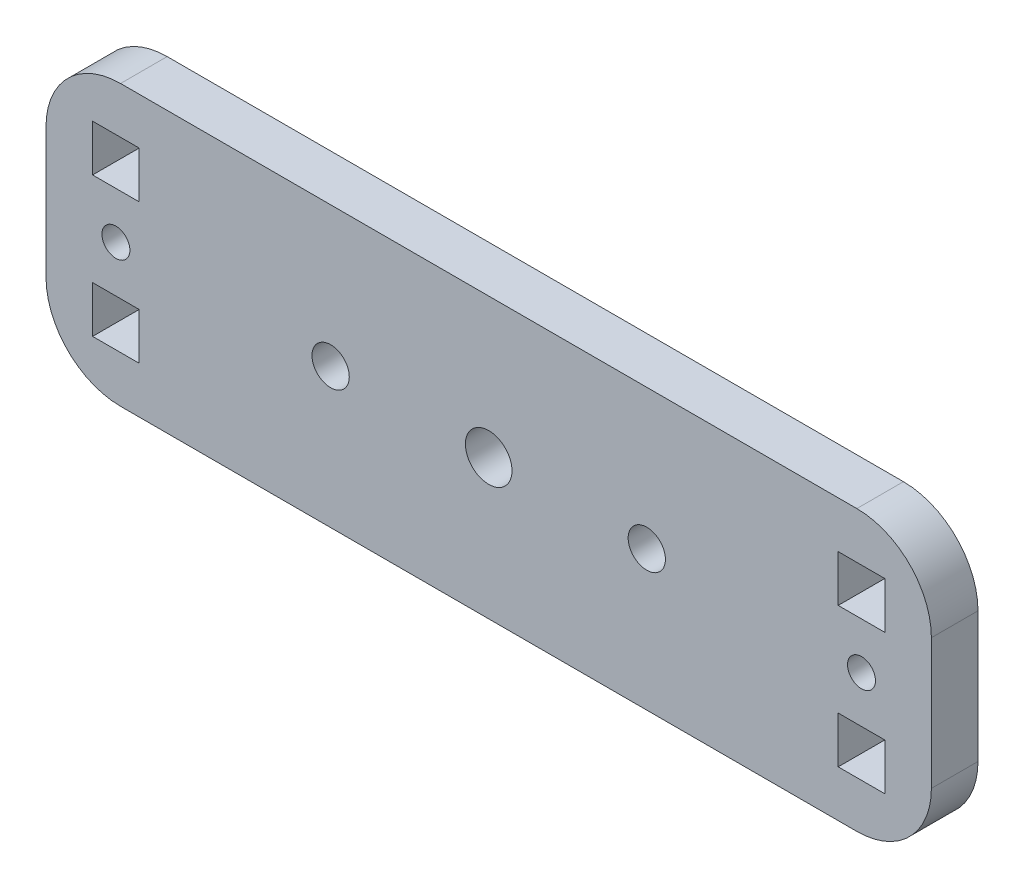
SolidWorks part; units mm, degrees
ref_plane "Plan de face" through (0, 0, 0) normal (0, 0, 1) x (1, 0, 0)
ref_plane "Plan de dessus" through (0, 0, 0) normal (0, 1, 0) x (1, 0, 0)
ref_plane "Plan de droite" through (0, 0, 0) normal (1, 0, 0) x (0, 0, -1)
sketch "Esquisse1" plane through (0, 0, 0) normal (0, 0, 1) x (1, 0, 0)
  line L0 (0, 15) -> (95, 15) construction
  line L1 (8, 0) -> (87, 0)
  line L2 (0, 8) -> (0, 22)
  line L3 (8, 30) -> (87, 30)
  line L4 (95, 8) -> (95, 22)
  line L5 (5, 25) -> (10, 25)
  line L6 (5, 25) -> (5, 20)
  line L7 (5, 20) -> (10, 20)
  line L8 (10, 25) -> (10, 20)
  line L17 (85, 25) -> (90, 25)
  line L18 (85, 25) -> (85, 20)
  line L19 (85, 20) -> (90, 20)
  line L20 (90, 25) -> (90, 20)
  line L21 (90, 5) -> (90, 10)
  line L22 (85, 10) -> (90, 10)
  line L23 (85, 5) -> (85, 10)
  line L24 (85, 5) -> (90, 5)
  line L33 (10, 5) -> (10, 10)
  line L34 (5, 10) -> (10, 10)
  line L35 (5, 5) -> (5, 10)
  line L36 (5, 5) -> (10, 5)
  line L37 (87.5, 20) -> (87.5, 10) construction
  line L38 (7.5, 20) -> (7.5, 10) construction
  arc A0 (8, 0) -> (0, 8) centre (8, 8) cw
  arc A1 (87, 0) -> (95, 8) centre (87, 8) ccw
  arc A2 (87, 30) -> (95, 22) centre (87, 22) cw
  arc A3 (0, 22) -> (8, 30) centre (8, 22) cw
  circle A4 centre (7.5, 15) radius 1.5
  circle A5 centre (87.5, 15) radius 1.5
  circle A6 centre (30.54, 15) radius 2
  circle A7 centre (64.46, 15) radius 2
  circle A8 centre (47.5, 15) radius 2.5
  point P7 (0, 0)
  point P12 (95, 30)
  point P15 (0, 30)
  dimension "D3" = 8
  dimension "D10" = 10
  dimension "D13" = 3
  dimension "D16" = 4
  dimension "D9" = 3
  dimension "D8" = 5
  dimension "D12" = 16.96
  dimension "D15" = 4
  dimension "D2" = 75
  dimension "D4" = 5
  dimension "D5" = 5
  dimension "D6" = 5
  dimension "D7" = 5
  dimension "D11" = 5
  dimension "D14" = 16.96
extrude "Boss.-Extru.1" add sketch "Esquisse1" along normal blind 5
